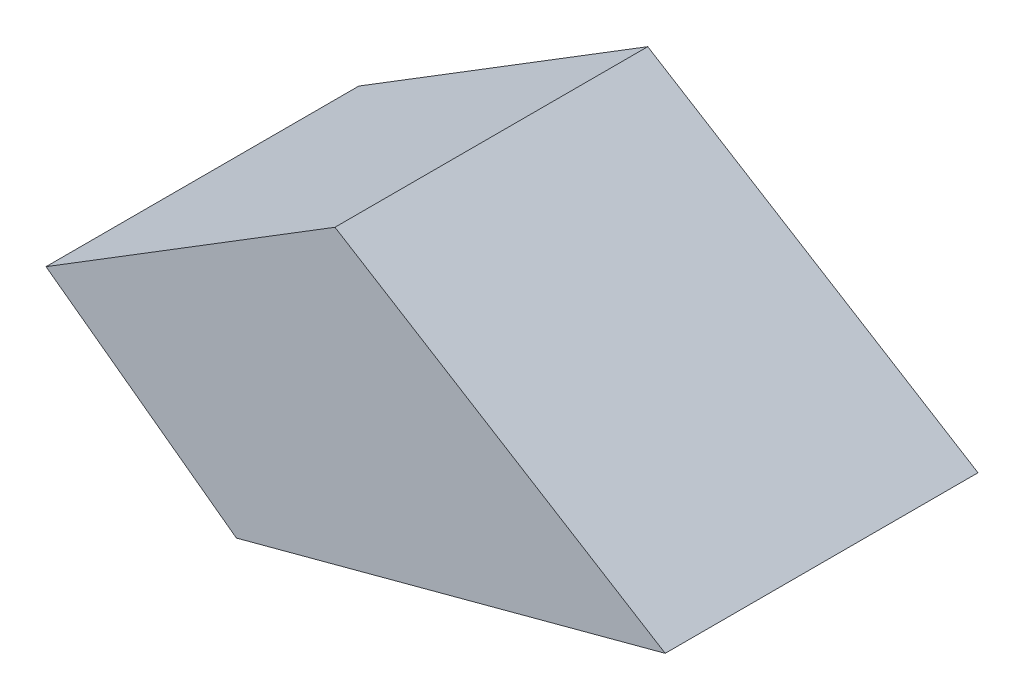
SolidWorks part; units mm, degrees
ref_plane "Front Plane" through (0, 0, 0) normal (0, 0, 1) x (1, 0, 0)
ref_plane "Top Plane" through (0, 0, 0) normal (0, 1, 0) x (1, 0, 0)
ref_plane "Right Plane" through (0, 0, 0) normal (1, 0, 0) x (0, 0, -1)
sketch "Sketch1" plane through (0, 0, 0) normal (0, 0, 1) x (1, 0, 0)
  line L0 (-77.9906, 12.588) -> (15.8718, 70.602)
  line L1 (15.8718, 70.602) -> (123.143, 4.3784)
  line L2 (123.143, 4.3784) -> (-16.1454, -32.8381)
  line L3 (-16.1454, -32.8381) -> (-77.9906, 12.588)
extrude "Boss-Extrude1" add sketch "Sketch1" against normal blind 101.6
